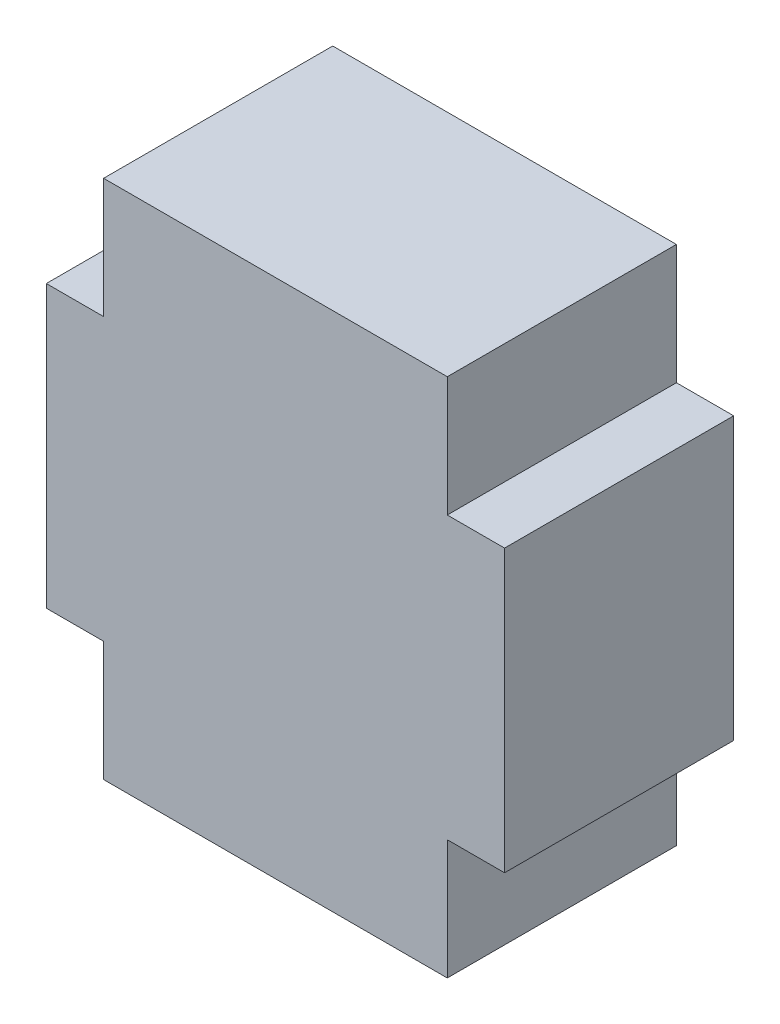
SolidWorks part; units mm, degrees
ref_plane "前视基准面" through (0, 0, 0) normal (0, 0, 1) x (1, 0, 0)
ref_plane "上视基准面" through (0, 0, 0) normal (0, 1, 0) x (1, 0, 0)
ref_plane "右视基准面" through (0, 0, 0) normal (1, 0, 0) x (0, 0, -1)
sketch "草图1" plane through (0, 0, 0) normal (0, 0, 1) x (1, 0, 0)
  line L0 (1.1, -0.675) -> (0.825, -0.675)
  line L1 (0.825, -0.675) -> (0.825, -1.25)
  line L2 (0.825, -1.25) -> (-0.825, -1.25)
  line L3 (-0.825, -1.25) -> (-0.825, -0.675)
  line L4 (-0.825, -0.675) -> (-1.1, -0.675)
  line L5 (-1.1, -0.675) -> (-1.1, 0.675)
  line L6 (-1.1, 0.675) -> (-0.825, 0.675)
  line L7 (-0.825, 0.675) -> (-0.825, 1.25)
  line L8 (-0.825, 1.25) -> (0.825, 1.25)
  line L9 (0.825, 1.25) -> (0.825, 0.675)
  line L10 (0.825, 0.675) -> (1.1, 0.675)
  line L11 (1.1, 0.675) -> (1.1, -0.675)
extrude "Component_Outline" add sketch "草图1" along normal blind 1.1 separate body
sketch3d "3D草图1"
  line L0 (0, 0, 0) -> (1, 0, 0)
  line L1 (0, 0, 0) -> (0, 1, 0)
  line L2 (0, 0, 0) -> (0, 0, 1)
  point P0 (0, 0, 0)
